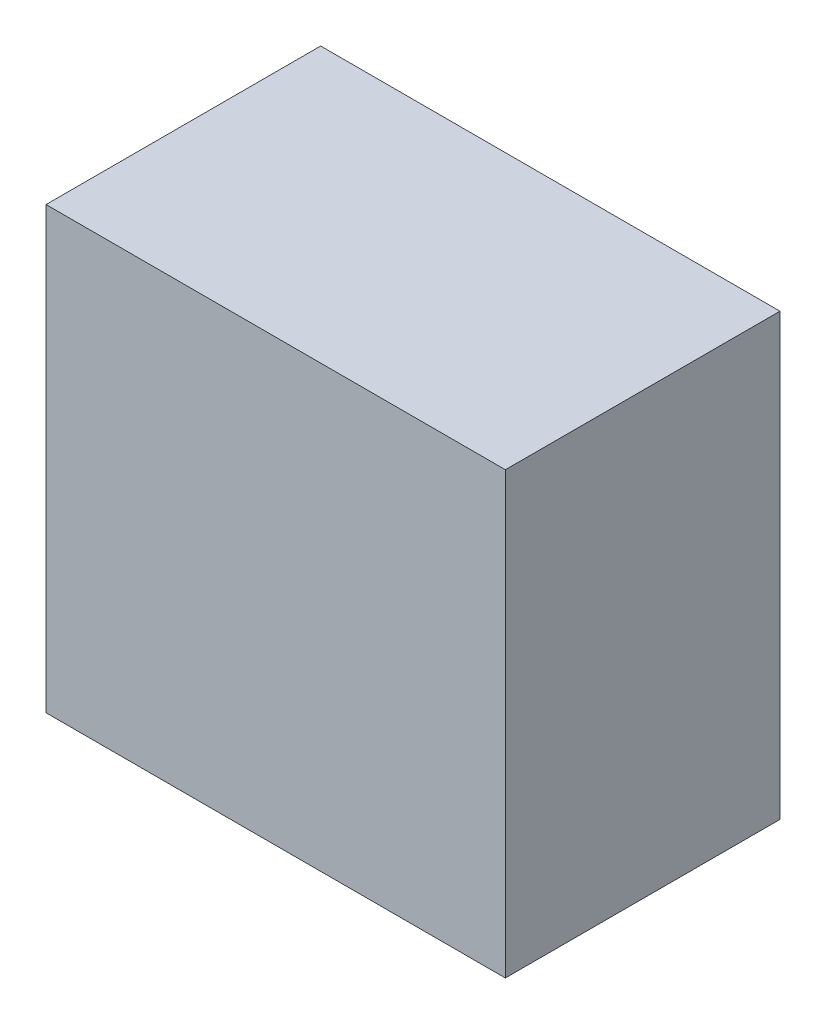
SolidWorks part; units mm, degrees
ref_plane "Plan de face" through (0, 0, 0) normal (0, 0, 1) x (1, 0, 0)
ref_plane "Plan de dessus" through (0, 0, 0) normal (0, 1, 0) x (1, 0, 0)
ref_plane "Plan de droite" through (0, 0, 0) normal (1, 0, 0) x (0, 0, -1)
sketch "Esquisse1" plane through (0, 0, 0) normal (0, 0, 1) x (1, 0, 0)
  line L0 (-7.527, 4.11) -> (7.527, 4.11)
  line L1 (7.527, 4.11) -> (7.527, -10.317)
  line L2 (7.527, -10.317) -> (-7.527, -10.317)
  line L3 (-7.527, -10.317) -> (-7.527, 4.11)
extrude "Component_Outline" add sketch "Esquisse1" along normal blind 9 separate body
sketch3d "Esquisse3D1"
  line L0 (0, 0, 0) -> (1, 0, 0)
  line L1 (0, 0, 0) -> (0, 1, 0)
  line L2 (0, 0, 0) -> (0, 0, 1)
  point P0 (0, 0, 0)
